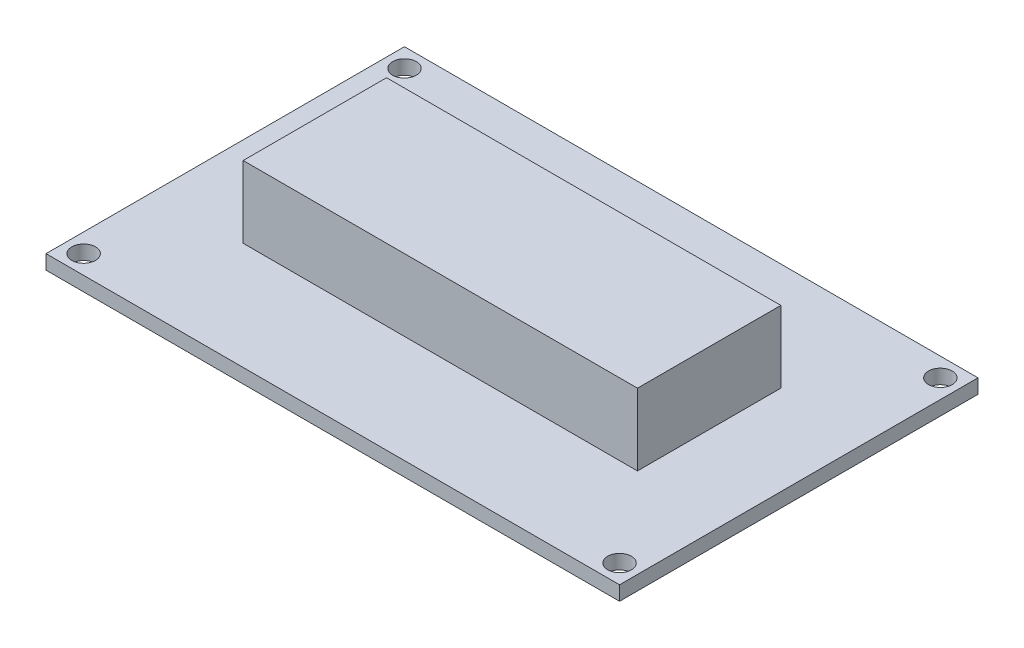
SolidWorks part; units mm, degrees
ref_plane "Front Plane" through (0, 0, 0) normal (0, 0, 1) x (1, 0, 0)
ref_plane "Top Plane" through (0, 0, 0) normal (0, 1, 0) x (1, 0, 0)
ref_plane "Right Plane" through (0, 0, 0) normal (1, 0, 0) x (0, 0, -1)
sketch "Sketch1" plane through (0, 0, 0) normal (0, 1, 0) x (1, 0, 0)
  line L0 (2.625, 47.375) -> (2.625, 50)
  line L1 (0, 0) -> (80, 0)
  line L2 (0, 0) -> (0, 50)
  line L3 (0, 50) -> (80, 50)
  line L4 (80, 0) -> (80, 50)
  line L5 (2.625, 2.625) -> (77.375, 2.625) construction
  line L6 (2.625, 2.625) -> (2.625, 47.375) construction
  line L7 (2.625, 47.375) -> (77.375, 47.375) construction
  line L8 (77.375, 2.625) -> (77.375, 47.375) construction
  line L9 (2.625, 2.625) -> (77.375, 47.375) construction
  line L10 (2.625, 47.375) -> (77.375, 2.625) construction
  line L11 (2.625, 47.375) -> (0, 47.375) construction
  line L12 (77.375, 2.625) -> (77.375, 0) construction
  line L13 (77.375, 2.625) -> (80, 2.625) construction
  circle A1 centre (2.625, 2.625) radius 1.65
  circle A2 centre (77.375, 2.625) radius 1.65
  circle A3 centre (2.625, 47.375) radius 1.65
  circle A4 centre (77.375, 47.375) radius 1.65
  point P11 (40, 25)
  dimension "D4" = 3.3
  dimension "D2" = 80
  dimension "D3" = 50
  dimension "D5" = 74.75
  dimension "D6" = 44.75
extrude "Boss-Extrude1" add sketch "Sketch1" along normal blind 2
sketch "Sketch2" plane through (0, 2, 0) normal (0, 1, 0) x (1, 0, 0)
  line L0 (12.5, 25) -> (0, 25) construction
  line L1 (12.5, 35) -> (67.5, 35)
  line L2 (12.5, 35) -> (12.5, 15)
  line L3 (12.5, 15) -> (67.5, 15)
  line L4 (67.5, 35) -> (67.5, 15)
  line L5 (12.5, 35) -> (67.5, 15) construction
  line L6 (12.5, 15) -> (67.5, 35) construction
  line L7 (0, 0) -> (0, 50) construction
  line L8 (40, 35) -> (40, 50) construction
  line L9 (0, 50) -> (80, 50) construction
  line L10 (40, 15) -> (40, 0) construction
  line L11 (0, 0) -> (80, 0) construction
  line L12 (67.5, 25) -> (80, 25) construction
  line L13 (80, 0) -> (80, 50) construction
  point P4 (40, 25)
  dimension "D1" = 55
  dimension "D2" = 20
extrude "Boss-Extrude2" add sketch "Sketch2" along normal blind 10
